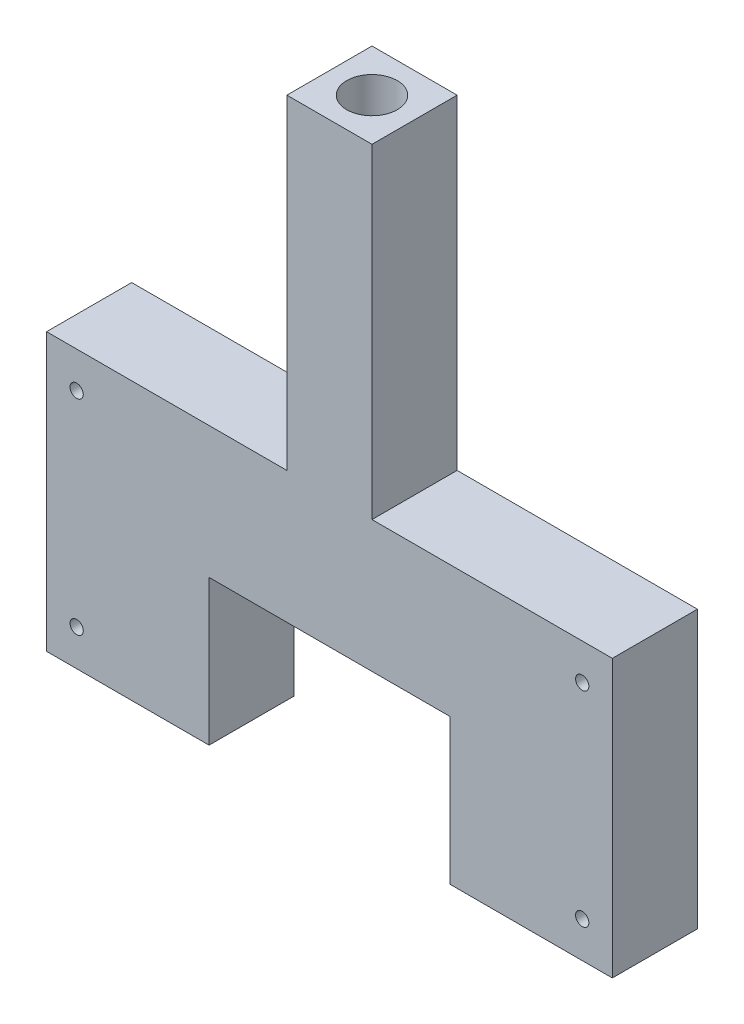
SolidWorks part; units mm, degrees
ref_plane "Front Plane" through (0, 0, 0) normal (0, 0, 1) x (1, 0, 0)
ref_plane "Top Plane" through (0, 0, 0) normal (0, 1, 0) x (1, 0, 0)
ref_plane "Right Plane" through (0, 0, 0) normal (1, 0, 0) x (0, 0, -1)
sketch "Esquisse1" plane through (0, 0, 0) normal (0, 0, 1) x (1, 0, 0)
  line L1 (-23.5, 11.5) -> (23.5, 11.5)
  line L2 (-23.5, 11.5) -> (-23.5, -11.5)
  line L3 (-23.5, -11.5) -> (23.5, -11.5)
  line L4 (23.5, 11.5) -> (23.5, -11.5)
  line L5 (-23.5, 11.5) -> (23.5, -11.5) construction
  line L6 (-23.5, -11.5) -> (23.5, 11.5) construction
  point P0 (0, 0)
  dimension "D1" = 47
  dimension "D2" = 23
extrude "Boss.-Extru.1" add sketch "Esquisse1" along normal blind 7.0711
sketch "Esquisse2" plane through (0, 0, 7.0711) normal (0, 0, 1) x (1, 0, 0)
  line L0 (-21, 8.5) -> (21, 8.5) construction
  line L1 (-22.5, 10) -> (22.5, 10) construction
  line L2 (-22.5, 10) -> (-22.5, -10) construction
  line L3 (-22.5, -10) -> (22.5, -10) construction
  line L4 (22.5, 10) -> (22.5, -10) construction
  line L5 (-22.5, 10) -> (22.5, -10) construction
  line L6 (-22.5, -10) -> (22.5, 10) construction
  line L7 (21, 8.5) -> (21, -8.5) construction
  line L8 (-21, -8.5) -> (21, -8.5) construction
  line L9 (-21, 8.5) -> (-21, -8.5) construction
  line L10 (-23.5, -11.5) -> (23.5, -11.5) construction
  line L11 (23.5, 11.5) -> (-23.5, 11.5) construction
  line L12 (23.5, -11.5) -> (23.5, 11.5) construction
  line L13 (-23.5, 11.5) -> (-23.5, -11.5) construction
  point P0 (0, 0)
  point P7 (-22.5, 10)
  point P8 (-22.5, -10)
  point P9 (22.5, 10)
  point P10 (22.5, -10)
  dimension "D1" = 45
  dimension "D2" = 20
  dimension "D4" = 17
  dimension "D5" = 42
  dimension "D6" = 8.5
  dimension "D7" = 8.5
  dimension "D8" = 3
  dimension "D9" = 3
  dimension "D10" = 2.5
  dimension "D11" = 2.5
  dimension "D3" = 1.5
hole_wizard "Trou taraudé M1.4x0.32" positions "Esquisse3D2" profile "Esquisse4" tap size "M1.4x0.3" standard "Ansi Metric" end condition through all
sketch3d "Esquisse3D2"
  point P0 (-21, 8.5, 7.0711)
  point P3 (-21, -8.5, 7.0711)
  point P6 (21, -8.5, 7.0711)
  point P9 (21, 8.5, 7.0711)
sketch "Esquisse4" plane through (-21, 8.5, 7.0711) normal (1, 0, 0) x (0, -1, 0)
  line L0 (0, 0) -> (0, 7.0711)
  line L1 (0, 7.0711) -> (0.55, 7.0711)
  line L2 (0.55, 7.0711) -> (0.55, 0)
  line L5 (0.55, 0) -> (0, 0)
  line L11 (0, -6.35) -> (0, 107.95) construction
  dimension "Diamètre du trou pour taraudage jusqu'au prochain" = 1.1
  dimension "Profondeur du trou pour taraudage jusqu'au prochain" = 7.0711
cosmetic thread "Filetage de perçage5" parameters "D2"=1.4
cosmetic thread "Filetage de perçage6" parameters "D2"=1.4
cosmetic thread "Filetage de perçage7" parameters "D2"=1.4
cosmetic thread "Filetage de perçage8" parameters "D2"=1.4
sketch "Esquisse5" plane through (0, 0, 7.0711) normal (0, 0, 1) x (1, 0, 0)
  line L0 (0, 11.5) -> (0, -12.8034) construction
  line L1 (23.5, 11.5) -> (-23.5, 11.5) construction
  line L3 (-10, 0.5726) -> (10, 0.5726)
  line L4 (-10, 0.5726) -> (-10, -14.4274)
  line L5 (-10, -14.4274) -> (10, -14.4274)
  line L6 (10, 0.5726) -> (10, -14.4274)
  line L7 (-10, 0.5726) -> (10, -14.4274) construction
  line L8 (-10, -14.4274) -> (10, 0.5726) construction
  point P5 (0, -6.9274)
  dimension "D1" = 15
  dimension "D2" = 20
extrude "Enlèv. mat.-Extru.1" cut sketch "Esquisse5" against normal up to surface (7.0711 mm away) up to face at (-20.45, 8.5, 0)
sketch "Esquisse6" plane through (0, 0, 0) normal (0, 0, -1) x (-1, 0, 0)
  line L0 (-23.5, 11.5) -> (23.5, 11.5) construction
  line L1 (-10, 0.5726) -> (10, 0.5726)
  line L2 (-10, 0.5726) -> (-10, 11.5)
  line L3 (-10, 11.5) -> (10, 11.5)
  line L4 (10, 0.5726) -> (10, 11.5)
extrude "Boss.-Extru.2" add sketch "Esquisse6" against normal up to surface (7.0711 mm away) up to face at (0, -2.7319, 7.0711)
sketch "Esquisse9" plane through (0, 11.5, 0) normal (0, 1, 0) x (1, 0, 0)
  line L6 (-3.5355, 0) -> (3.5355, 0)
  line L7 (-3.5355, 0) -> (-3.5355, -7.0711)
  line L8 (-3.5355, -7.0711) -> (3.5355, -7.0711)
  line L9 (3.5355, 0) -> (3.5355, -7.0711)
  line L10 (-3.5355, 0) -> (3.5355, -7.0711) construction
  line L11 (-3.5355, -7.0711) -> (3.5355, 0) construction
  line L12 (-23.5, -3.5355) -> (24.2626, -3.5355) construction
  line L13 (-23.5, -7.0711) -> (-23.5, 0) construction
  line L14 (0, -7.0711) -> (0, 3.2197) construction
  line L15 (23.5, -7.0711) -> (-23.5, -7.0711) construction
  point P0 (0, -3.5355)
  point P18 (0, -3.5355)
  dimension "D1" = 10
  dimension "D2" = 7.0711
  dimension "D3" = 7.0711
extrude "Boss.-Extru.5" add sketch "Esquisse9" along normal blind 27
sketch "Esquisse10" plane through (0, 38.5, 0) normal (0, 1, 0) x (1, 0, 0)
  line L0 (3.5355, -3.5355) -> (-4.5405, -3.5355) construction
  line L1 (3.5355, -7.0711) -> (3.5355, 0) construction
  line L2 (0, 2.058) -> (0, -7.8512) construction
  circle A0 centre (0, -3.5355) radius 1.5
  dimension "D1" = 3
extrude "Enlèv. mat.-Extru.2" cut sketch "Esquisse10" against normal blind 3
hole_wizard "Trou taraudé M5x0.81" positions "Esquisse3D3" profile "Esquisse11" tap size "M5x0.8" standard "Ansi Metric"
sketch3d "Esquisse3D3"
  line L0 (0, 35.5, 3.5355) -> (0, 38.5, 3.5355) construction
  point P0 (0, 38.5, 3.5355)
sketch "Esquisse11" plane through (0, 38.5, 3.5355) normal (1, 0, 0) x (0, 0, 1)
  line L0 (0, 0) -> (0, 16.2618)
  line L1 (0, 16.2618) -> (2.1, 15)
  line L2 (2.1, 15) -> (2.1, 0)
  line L5 (2.1, 0) -> (0, 0)
  line L10 (0, 16.2618) -> (-2.1, 15) construction
  line L11 (0, -6.35) -> (0, 107.95) construction
  dimension "Diamètre du trou pour taraudage" = 4.2
  dimension "Profondeur du trou pour taraudage" = 15
  dimension "Angle de pointe" = 118
cosmetic thread "Filetage de perçage9" parameters "D1"=15, "D2"=5
